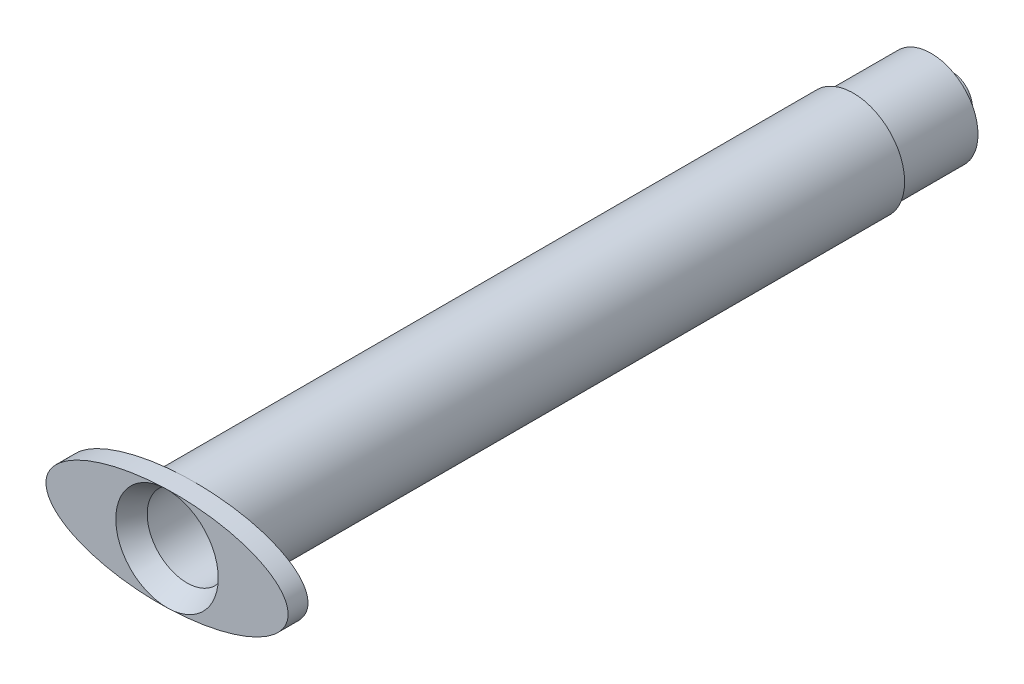
SolidWorks part; units mm, degrees
ref_plane "Front Plane" through (0, 0, 0) normal (0, 0, 1) x (1, 0, 0)
ref_plane "Top Plane" through (0, 0, 0) normal (0, 1, 0) x (1, 0, 0)
ref_plane "Right Plane" through (0, 0, 0) normal (1, 0, 0) x (0, 0, -1)
sketch "Sketch1" plane through (0, 0, 0) normal (0, 0, 1) x (1, 0, 0)
  circle A0 centre (0, 0) radius 4.1
  circle A1 centre (0, 0) radius 5.17
extrude "Boss-Extrude1" add sketch "Sketch1" along normal blind 67.25
sketch "Sketch2" plane through (0, 0, 67.25) normal (0, 0, 1) x (1, 0, 0)
  circle A0 centre (0, 0) radius 5.17 construction
  ellipse E0 centre (0, 0) end of major axis (-12.2124, -0.4308) minor radius 5.17
extrude "Boss-Extrude2" add sketch "Sketch2" along normal blind 2.01
sketch "Sketch3" plane through (0, 0, 69.26) normal (0, 0, 1) x (1, 0, 0)
  circle A0 centre (0, 0) radius 5.17
extrude "Cut-Extrude1" cut sketch "Sketch3" against normal blind 2.01 draft 30
sketch "Sketch4" plane through (0, 0, 0) normal (0, 0, -1) x (-1, 0, 0)
  circle A0 centre (0, 0) radius 0.795
  circle A1 centre (0, 0) radius 2.06
extrude "Boss-Extrude3" add sketch "Sketch4" along normal blind 9.95 separate body
sketch "Sketch5" plane through (0, 0, 0) normal (0, 0, -1) x (-1, 0, 0)
  circle A0 centre (0, 0) radius 4.0953
  dimension "D1" = 8.1905
extrude "Boss-Extrude4" add sketch "Sketch5" along normal blind 1.15
sketch "Sketch7" plane through (0, 0, -9.95) normal (0, 0, -1) x (-1, 0, 0)
  circle A0 centre (0, 0) radius 0.795
extrude "Cut-Extrude2" cut sketch "Sketch7" against normal through all
sketch "Sketch8" plane through (0, 0, 0) normal (0, 0, -1) x (-1, 0, 0)
sketch "Sketch9" plane through (0, 0, 0) normal (0, 0, -1) x (-1, 0, 0)
  circle A0 centre (0, 0) radius 4.11
  circle A1 centre (0, 0) radius 4.725
extrude "Boss-Extrude6" add sketch "Sketch9" along normal blind 7.85
